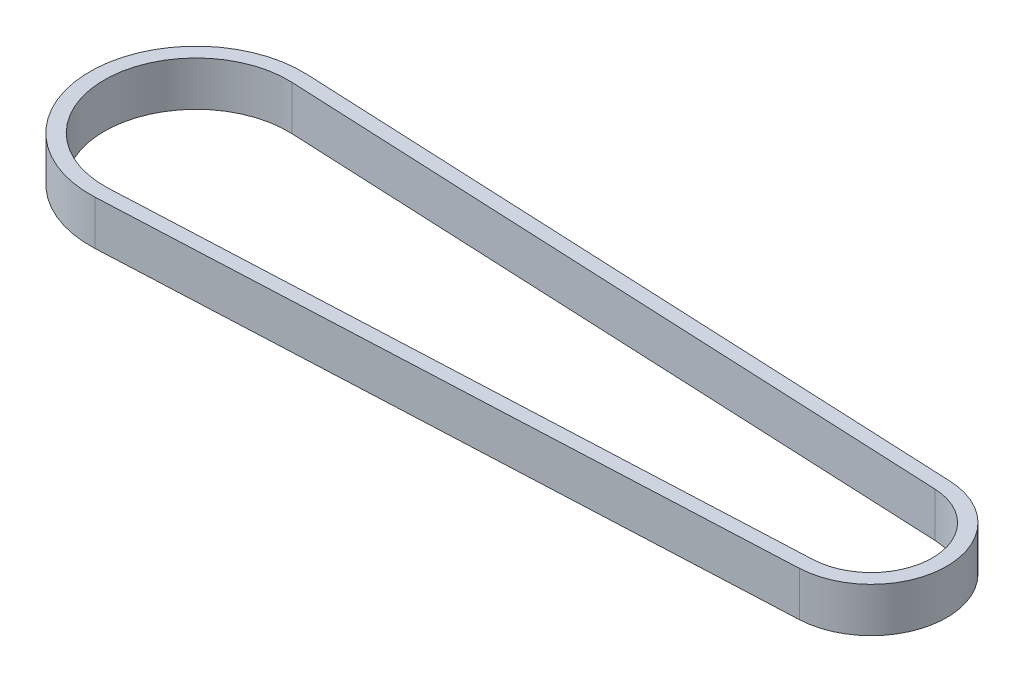
SolidWorks part; units mm, degrees
ref_plane "Front Plane" through (0, 0, 0) normal (0, 0, 1) x (1, 0, 0)
ref_plane "Top Plane" through (0, 0, 0) normal (0, 1, 0) x (1, 0, 0)
ref_plane "Right Plane" through (0, 0, 0) normal (1, 0, 0) x (0, 0, -1)
sketch "Sketch1" plane through (0, 0, 0) normal (0, 1, 0) x (1, 0, 0)
  line L0 (-70.2014, 0) -> (0, 0) construction
  line L1 (0, 0) -> (70.2014, 0) construction
  line L2 (-69.3308, 19.0801) -> (70.7803, 12.6868)
  line L3 (-69.3308, -19.0801) -> (70.7803, -12.6868)
  line L4 (-69.194, 22.077) -> (70.917, 15.6837)
  line L5 (-69.194, -22.077) -> (70.917, -15.6837)
  circle A0 centre (-70.2014, 0) radius 19.1 construction
  circle A1 centre (70.2014, 0) radius 12.7 construction
  arc A2 (70.7803, 12.6868) -> (70.7803, -12.6868) centre (70.2014, 0) cw
  arc A3 (-69.3308, 19.0801) -> (-69.3308, -19.0801) centre (-70.2014, 0) ccw
  arc A4 (70.917, 15.6837) -> (70.917, -15.6837) centre (70.2014, 0) cw
  arc A5 (-69.194, 22.077) -> (-69.194, -22.077) centre (-70.2014, 0) ccw
  point P3 (135.4303, 20.5634)
  point P4 (0, 0)
  point P14 (127.1006, -21.5968)
  dimension "D1" = 38.2
  dimension "D2" = 25.4
  dimension "D3" = 381
  dimension "D4" = 3
extrude "Boss-Extrude1" add sketch "Sketch1" along normal blind 9.25
